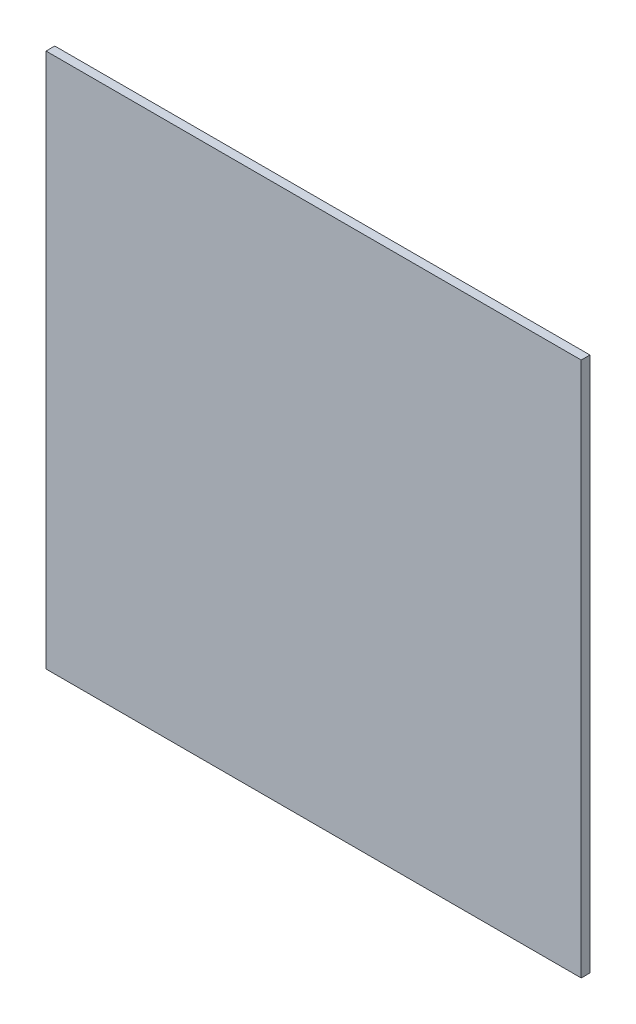
SolidWorks part; units mm, degrees
ref_plane "Front Plane" through (0, 0, 0) normal (0, 0, 1) x (1, 0, 0)
ref_plane "Top Plane" through (0, 0, 0) normal (0, 1, 0) x (1, 0, 0)
ref_plane "Right Plane" through (0, 0, 0) normal (1, 0, 0) x (0, 0, -1)
sketch "Sketch1" plane through (0, 0, 0) normal (0, 0, 1) x (1, 0, 0)
  line L1 (0, 0) -> (98, 0)
  line L2 (0, 0) -> (0, 98)
  line L3 (0, 98) -> (98, 98)
  line L4 (98, 0) -> (98, 98)
  dimension "D1" = 98
  dimension "D2" = 98
extrude "Boss-Extrude1" add sketch "Sketch1" along normal blind 1.6
